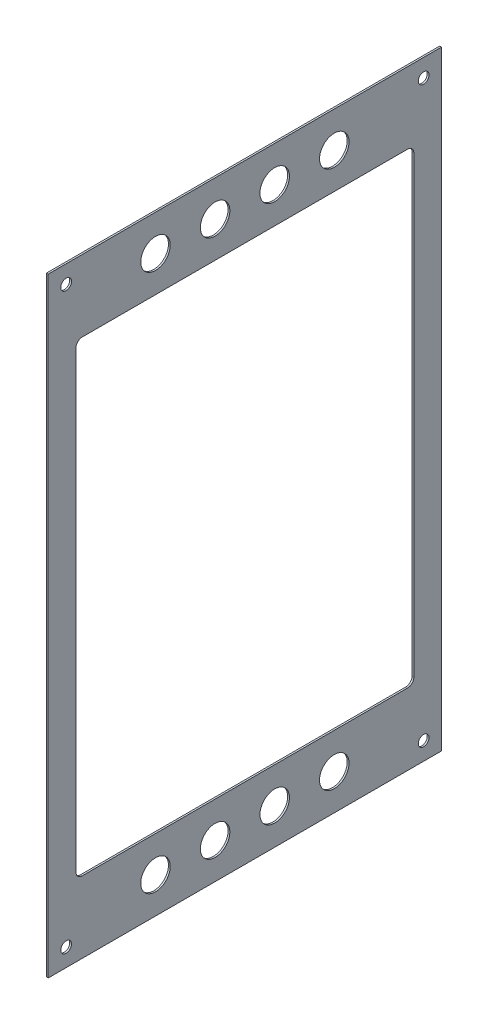
SolidWorks part; units mm, degrees
ref_plane "Front Plane" through (0, 0, 0) normal (1, 0, 0) x (0, 1, 0)
ref_plane "Top Plane" through (0, 0, 0) normal (0, 0, 1) x (0, 1, 0)
ref_plane "Right Plane" through (0, 0, 0) normal (0, 1, 0) x (-1, 0, 0)
sketch "Sketch1" plane through (0, 0, 0) normal (1, 0, 0) x (0, 1, 0)
  line L1 (-170.5, -110) -> (170.5, -110)
  line L2 (-170.5, -110) -> (-170.5, 110)
  line L3 (-170.5, 110) -> (170.5, 110)
  line L4 (170.5, -110) -> (170.5, 110)
  line L5 (-170.5, -110) -> (170.5, 110) construction
  line L6 (-170.5, 110) -> (170.5, -110) construction
  point P0 (0, 0)
  dimension "D1" = 341
  dimension "D2" = 220
extrude "Boss-Extrude1" add sketch "Sketch1" along normal blind 1
sketch "Sketch2" plane through (1, 0, 0) normal (1, 0, 0) x (0, 1, 0)
  line L8 (-170.5, 0) -> (170.5, 0) construction
  line L9 (-170.5, 110) -> (-170.5, -110) construction
  line L10 (170.5, -110) -> (170.5, 110) construction
  line L11 (150.5026, 110) -> (150.5026, -110) construction
  line L12 (-130.5026, 91.0027) -> (-130.5026, -91.0027)
  line L13 (-127.0027, -94.5026) -> (127.0027, -94.5026)
  line L14 (130.5026, -91.0027) -> (130.5026, 91.0027)
  line L15 (127.0027, 94.5026) -> (-127.0027, 94.5026)
  line L16 (-130.5026, 91.0027) -> (-130.5026, -91.0027)
  line L17 (-127.0027, -94.5026) -> (127.0027, -94.5026)
  line L18 (130.5026, -91.0027) -> (130.5026, 91.0027)
  line L19 (127.0027, 94.5026) -> (-127.0027, 94.5026)
  line L20 (170.5, 110) -> (-170.5, 110) construction
  line L21 (0, 110) -> (0, -110) construction
  line L22 (-170.5, -110) -> (170.5, -110) construction
  circle A0 centre (150.5026, 50) radius 8.25
  arc A1 (-127.0027, 94.5026) -> (-130.5026, 91.0027) centre (-127.0027, 91.0027) ccw
  arc A2 (-130.5026, -91.0027) -> (-127.0027, -94.5026) centre (-127.0027, -91.0027) ccw
  arc A3 (127.0027, -94.5026) -> (130.5026, -91.0027) centre (127.0027, -91.0027) ccw
  arc A4 (130.5026, 91.0027) -> (127.0027, 94.5026) centre (127.0027, 91.0027) ccw
  arc A5 (-127.0027, 94.5026) -> (-130.5026, 91.0027) centre (-127.0027, 91.0027) ccw
  arc A6 (-130.5026, -91.0027) -> (-127.0027, -94.5026) centre (-127.0027, -91.0027) ccw
  arc A7 (127.0027, -94.5026) -> (130.5026, -91.0027) centre (127.0027, -91.0027) ccw
  arc A8 (130.5026, 91.0027) -> (127.0027, 94.5026) centre (127.0027, 91.0027) ccw
  circle A11 centre (150.5026, 16.67) radius 8.25
  circle A12 centre (150.5026, -16.67) radius 8.25
  circle A13 centre (150.5026, -50) radius 8.25
  circle A14 centre (-150.5026, -50) radius 8.25
  circle A15 centre (-150.5026, -16.67) radius 8.25
  circle A16 centre (-150.5026, 16.67) radius 8.25
  circle A17 centre (-150.5026, 50) radius 8.25
  dimension "D3" = 16.5
  dimension "D4" = 50
  dimension "D2" = 20
  dimension "D5" = 16.67
  dimension "D1" = 0.5
extrude "Cut-Extrude1" cut sketch "Sketch2" against normal through all
sketch "Sketch3" plane through (1, 0, 0) normal (1, 0, 0) x (0, 1, 0)
  line L0 (0, 110) -> (0, -110) construction
  line L1 (170.5, 110) -> (-170.5, 110) construction
  line L2 (-170.5, -110) -> (170.5, -110) construction
  line L3 (0, -110) -> (170.5, 0) construction
  line L4 (170.5, -110) -> (170.5, 110) construction
  line L5 (170.5, 0) -> (-170.5, 0) construction
  line L6 (-170.5, 110) -> (-170.5, -110) construction
  circle A0 centre (-160.5, 100) radius 3
  circle A1 centre (160.5, 100) radius 3
  circle A2 centre (-160.5, -100) radius 3
  circle A3 centre (160.5, -100) radius 3
  dimension "D3" = 6
  dimension "D1" = 10
  dimension "D2" = 10
extrude "Cut-Extrude2" cut sketch "Sketch3" against normal through all
